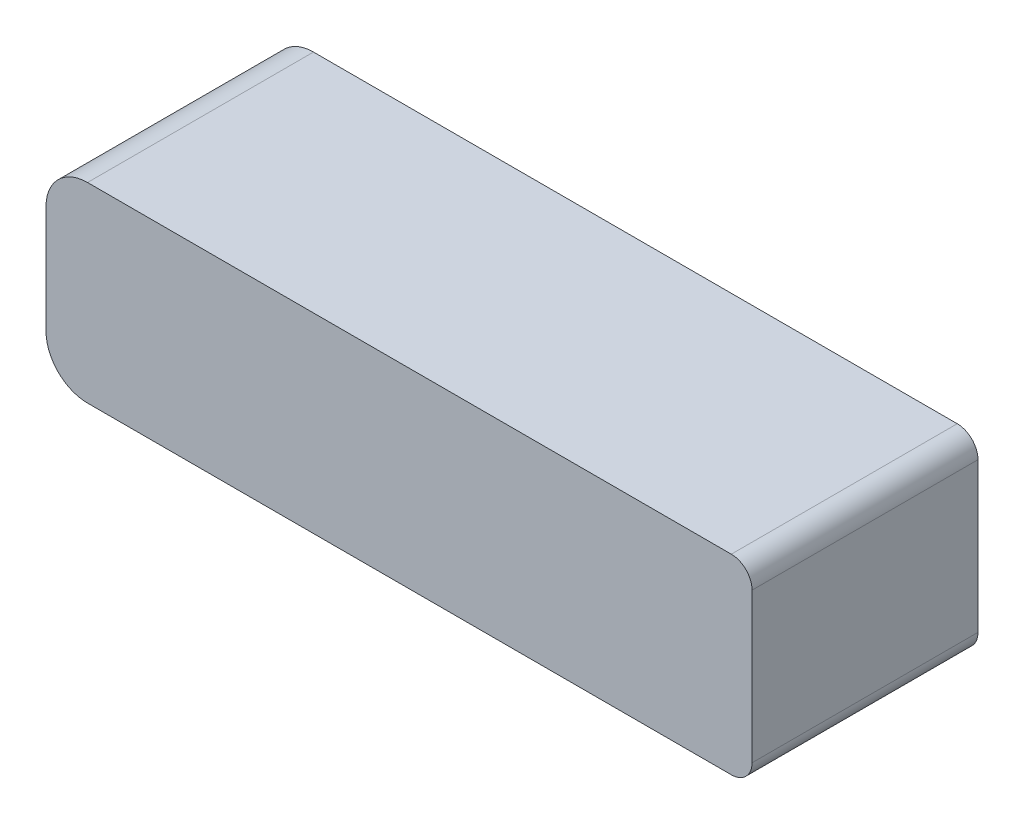
SolidWorks part; units mm, degrees
ref_plane "Front Plane" through (0, 0, 0) normal (0, 0, 1) x (1, 0, 0)
ref_plane "Top Plane" through (0, 0, 0) normal (0, 1, 0) x (1, 0, 0)
ref_plane "Right Plane" through (0, 0, 0) normal (1, 0, 0) x (0, 0, -1)
sketch "Sketch1" plane through (0, 0, 0) normal (0, 1, 0) x (1, 0, 0)
  line L0 (-53.975, 17.272) -> (53.975, 17.272)
  line L1 (53.975, 17.272) -> (53.975, -17.272)
  line L2 (53.975, -17.272) -> (-53.975, -17.272)
  line L3 (-53.975, -17.272) -> (-53.975, 17.272)
  point P2 (0, 17.272)
  point P5 (-53.975, 0)
  dimension "D1" = 107.95
  dimension "D2" = 34.544
extrude "Boss-Extrude1" add sketch "Sketch1" along normal blind 14.605 and the other way blind 14.605
fillet "Fillet1" radius 3.175 2 edges at (53.975, -14.605, 0) (53.975, 14.605, 0)
fillet "Fillet2" radius 6.35 2 edges at (-53.975, -14.605, 0) (-53.975, 14.605, 0)
